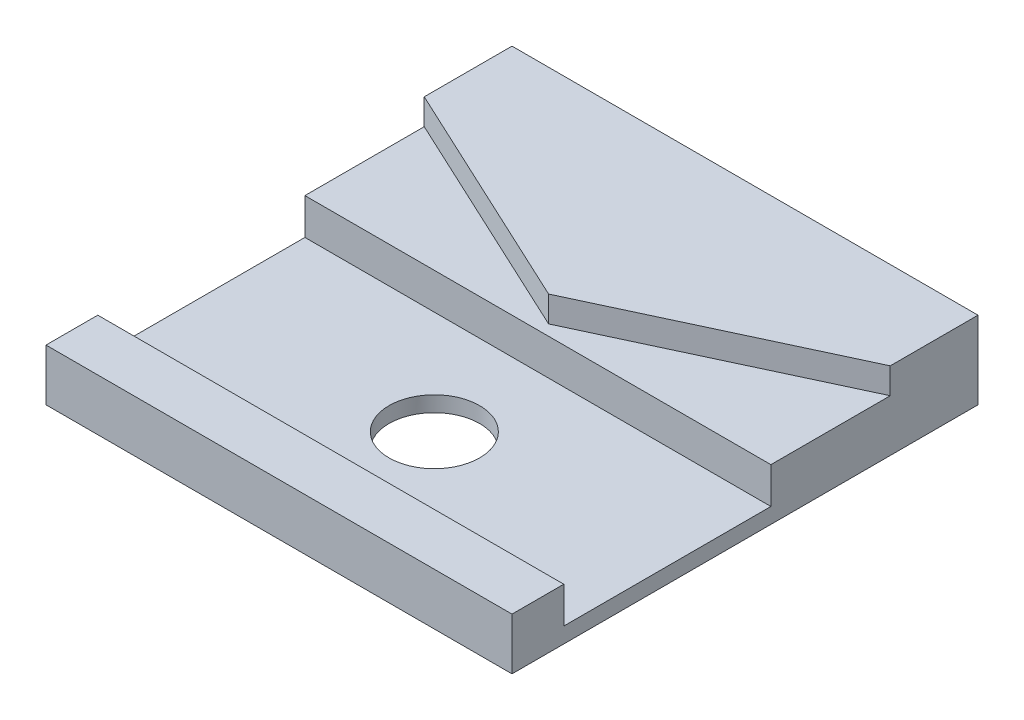
SolidWorks part; units mm, degrees
ref_plane "Front" through (0, 0, 0) normal (0, 0, 1) x (1, 0, 0)
ref_plane "Top" through (0, 0, 0) normal (0, 1, 0) x (1, 0, 0)
ref_plane "Right" through (0, 0, 0) normal (1, 0, 0) x (0, 0, -1)
sketch "Sketch1" plane through (0, 0, 0) normal (0, 1, 0) x (1, 0, 0)
  line L1 (-28.575, -28.575) -> (28.575, -28.575)
  line L2 (-28.575, -28.575) -> (-28.575, 28.575)
  line L3 (-28.575, 28.575) -> (28.575, 28.575)
  line L4 (28.575, -28.575) -> (28.575, 28.575)
  line L5 (-28.575, -28.575) -> (28.575, 28.575) construction
  line L6 (-28.575, 28.575) -> (28.575, -28.575) construction
  point P0 (0, 0)
  dimension "D1" = 57.15
  dimension "D2" = 57.15
extrude "Boss-Extrude1" add sketch "Sketch1" along normal blind 9.525 contours L3 L4 L1 L2
sketch "Sketch2" plane through (0, 9.525, 0) normal (0, 1, 0) x (1, 0, 0)
  line L0 (28.575, -28.575) -> (28.575, 28.575) construction
  line L1 (28.575, 3.175) -> (-28.575, 3.175)
  line L2 (28.575, 3.175) -> (28.575, -22.225)
  line L3 (28.575, -22.225) -> (-28.575, -22.225)
  line L4 (-28.575, 3.175) -> (-28.575, -22.225)
  line L5 (-28.575, -28.575) -> (-28.575, 28.575) construction
  line L6 (-28.575, -28.575) -> (28.575, -28.575) construction
  dimension "D1" = 25.4
  dimension "D2" = 6.35
extrude "Cut-Extrude1" cut sketch "Sketch2" against normal blind 7.62
sketch "Sketch3" plane through (0, 1.905, 0) normal (0, 1, 0) x (1, 0, 0)
  line L0 (0, -50) -> (0, 50) construction
  line L1 (28.575, -22.225) -> (28.575, 3.175) construction
  point P0 (0, -9.525)
  point P1 (0, 0)
  point P6 (28.575, -9.525)
hole_wizard "7/16 (0.4375) Diameter Hole1" positions "Sketch4" profile "Sketch6" hole size "7/16" standard "ANSI Inch"
sketch "Sketch4" plane through (0, 1.905, 0) normal (0, 1, 0) x (1, 0, 0)
  point P0 (0, -9.525)
sketch "Sketch6" plane through (0, 1.905, 9.525) normal (1, 0, 0) x (0, 0, 1)
  line L0 (0, 0) -> (0, 28.7385)
  line L1 (0, 28.7385) -> (5.5562, 25.4)
  line L2 (5.5562, 25.4) -> (5.5562, 0)
  line L5 (5.5562, 0) -> (0, 0)
  line L10 (0, 28.7385) -> (-5.5563, 25.4) construction
  line L11 (0, -6.35) -> (0, 107.95) construction
  dimension "Hole Dia." = 11.1125
  dimension "Hole Depth" = 25.4
  dimension "Drill Angle" = 118
sketch "Sketch8" plane through (0, 9.525, 0) normal (0, 1, 0) x (1, 0, 0)
  line L0 (-36.1856, -12.3857) -> (25.4511, 16.3559) construction
  line L1 (-36.1856, -12.3857) -> (-25.4511, -35.4059) construction
  line L2 (25.4511, 16.3559) -> (36.1856, -6.6643) construction
  line L3 (-25.4511, -35.4059) -> (36.1856, -6.6643) construction
  line L4 (-36.1856, -12.3857) -> (36.1856, -6.6643) construction
  line L5 (25.4511, 16.3559) -> (-25.4511, -35.4059) construction
  line L6 (30.8183, 4.8458) -> (-30.8183, -23.8958) construction
  line L8 (28.575, -9.525) -> (-28.575, -9.525) construction
  line L9 (28.575, -22.225) -> (28.575, 3.175) construction
  line L10 (-28.575, 3.175) -> (-28.575, -22.225) construction
  line L14 (0, -50) -> (0, 50) construction
  line L15 (0, 4.4879) -> (28.575, 17.8126)
  line L16 (28.575, 3.175) -> (28.575, 28.575) construction
  line L18 (28.575, 17.8126) -> (28.575, 3.175)
  line L19 (28.575, 3.175) -> (0, 3.175)
  line L20 (28.575, 3.175) -> (-28.575, 3.175) construction
  line L21 (0, 3.175) -> (0, 4.4879)
  point P1 (0, -9.525)
  dimension "D1" = 25.4
  dimension "D2" = 68.0085
  dimension "D3" = 25
extrude "Cut-Extrude3" cut sketch "Sketch8" against normal blind 3.175
mirror "Mirror2" about plane through (0, 0, 0) normal (1, 0, 0) of "Cut-Extrude3"
sketch "Sketch9" plane through (0, 9.525, 0) normal (0, 1, 0) x (1, 0, 0)
  line L4 (28.575, -28.575) -> (28.575, -22.225)
  line L5 (28.575, -22.225) -> (-28.575, -22.225)
  line L6 (-28.575, -22.225) -> (-28.575, -28.575)
  line L7 (-28.575, -28.575) -> (28.575, -28.575)
  line L8 (28.575, -28.575) -> (28.575, -22.225)
  line L9 (28.575, -22.225) -> (-28.575, -22.225)
  line L10 (-28.575, -22.225) -> (-28.575, -28.575)
  line L11 (-28.575, -28.575) -> (28.575, -28.575)
  dimension "D1" = 0
extrude "Cut-Extrude4" cut sketch "Sketch9" against normal blind 3.175
